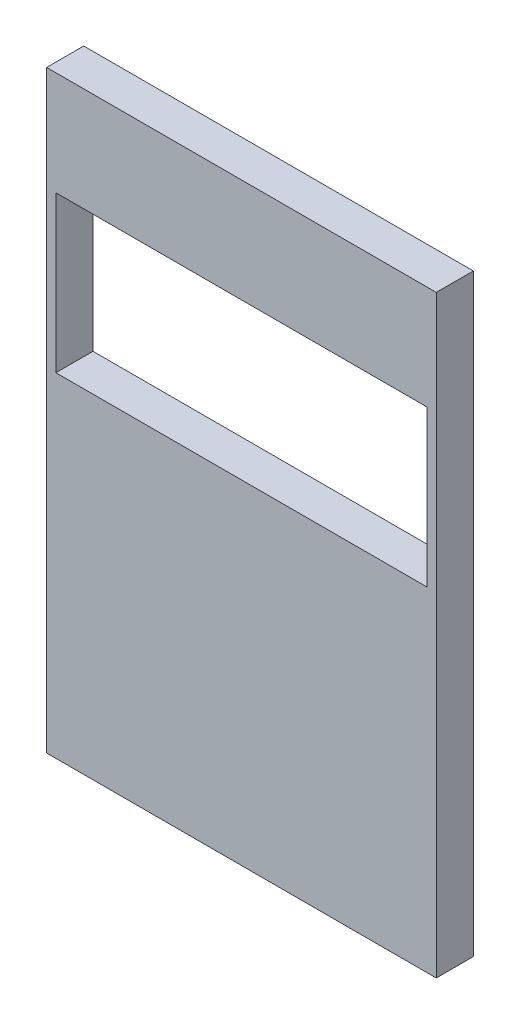
SolidWorks part; units mm, degrees
ref_plane "Front Plane" through (0, 0, 0) normal (0, 0, 1) x (1, 0, 0)
ref_plane "Top Plane" through (0, 0, 0) normal (0, 1, 0) x (1, 0, 0)
ref_plane "Right Plane" through (0, 0, 0) normal (1, 0, 0) x (0, 0, -1)
sketch "Sketch1" plane through (0, 0, 0) normal (0, 0, 1) x (1, 0, 0)
  line L1 (52.5, -80) -> (-52.5, -80)
  line L2 (52.5, -80) -> (52.5, 80)
  line L3 (52.5, 80) -> (-52.5, 80)
  line L4 (-52.5, -80) -> (-52.5, 80)
  line L5 (52.5, -80) -> (-52.5, 80) construction
  line L6 (52.5, 80) -> (-52.5, -80) construction
  point P0 (0, 0)
  dimension "D1" = 160
  dimension "D2" = 105
extrude "Boss-Extrude1" add sketch "Sketch1" along normal blind 10
sketch "Sketch3" plane through (0, 0, 0) normal (0, 0, -1) x (-1, 0, 0)
  line L1 (50, 10) -> (-50, 10)
  line L2 (50, 10) -> (50, 52)
  line L3 (50, 52) -> (-50, 52)
  line L4 (-50, 10) -> (-50, 52)
  line L5 (50, 10) -> (-50, 52) construction
  line L6 (50, 52) -> (-50, 10) construction
  line L7 (-52.5, 80) -> (52.5, 80) construction
  point P0 (0, 31)
  dimension "D1" = 49
  dimension "D2" = 42
  dimension "D3" = 100
extrude "Cut-Extrude1" cut sketch "Sketch3" against normal through all contours L3 L4 L1 L2
